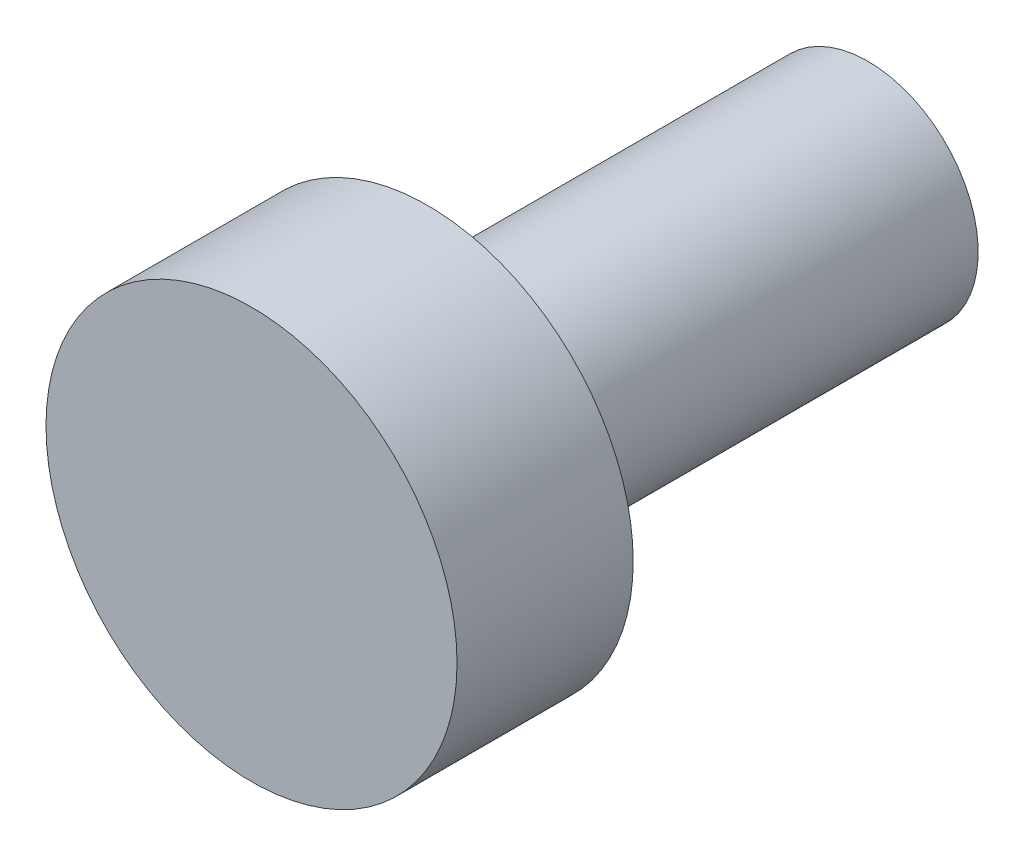
SolidWorks part; units mm, degrees
ref_plane "Plan de face" through (0, 0, 0) normal (0, 0, 1) x (1, 0, 0)
ref_plane "Plan de dessus" through (0, 0, 0) normal (0, 1, 0) x (1, 0, 0)
ref_plane "Plan de droite" through (0, 0, 0) normal (1, 0, 0) x (0, 0, -1)
sketch "Esquisse1" plane through (0, 0, 0) normal (0, 0, 1) x (1, 0, 0)
  circle A0 centre (0, 0) radius 2.8
  dimension "D1" = 5.6
extrude "Boss.-Extru.1" add sketch "Esquisse1" along normal blind 2.4
sketch "Esquisse2" plane through (0, 0, 0) normal (0, 0, -1) x (-1, 0, 0)
  circle A0 centre (0, 0) radius 1.5
  dimension "D1" = 3
extrude "Boss.-Extru.2" add sketch "Esquisse2" along normal blind 6
